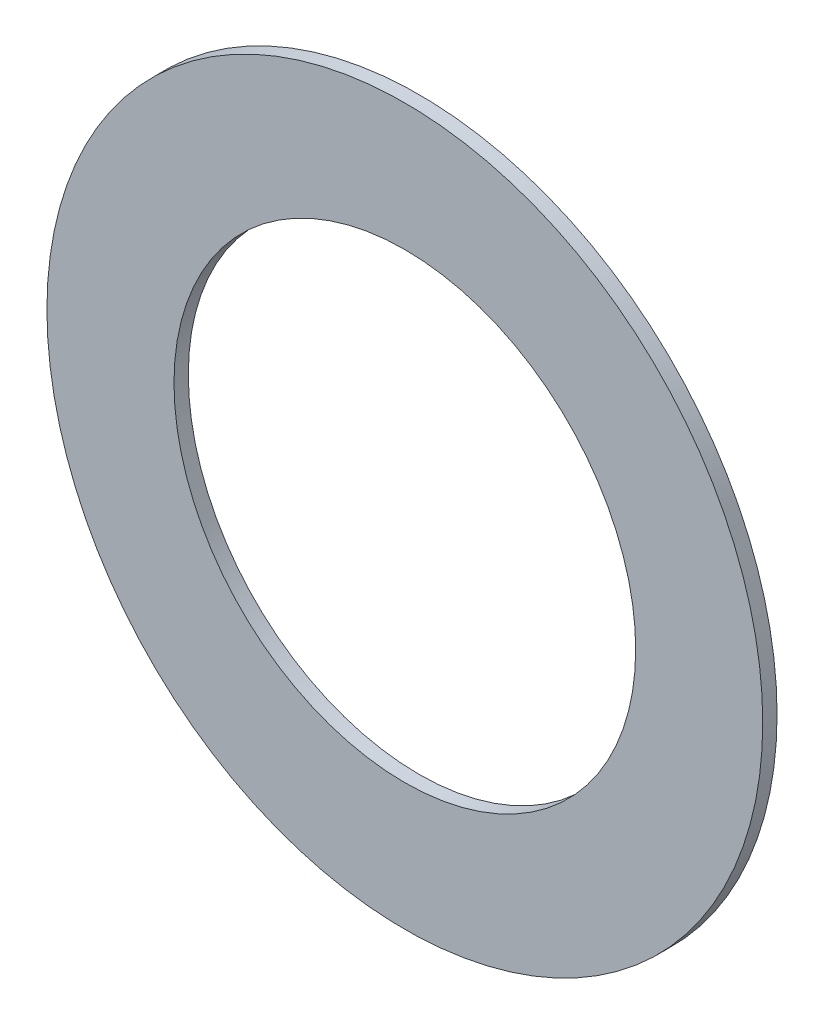
SolidWorks part; units mm, degrees
ref_plane "Front Plane" through (0, 0, 0) normal (0, 0, 1) x (1, 0, 0)
ref_plane "Top Plane" through (0, 0, 0) normal (0, 1, 0) x (1, 0, 0)
ref_plane "Right Plane" through (0, 0, 0) normal (1, 0, 0) x (0, 0, -1)
sketch "Sketch1" plane through (0, 0, 0) normal (0, 0, 1) x (1, 0, 0)
  circle A0 centre (0, 0) radius 31.75
  circle A1 centre (0, 0) radius 20.4788
  circle A2 centre (0, 0) radius 31.75 construction
  dimension "D2" = 40.9575
extrude "Boss-Extrude1" add sketch "Sketch1" along normal blind 1.27
